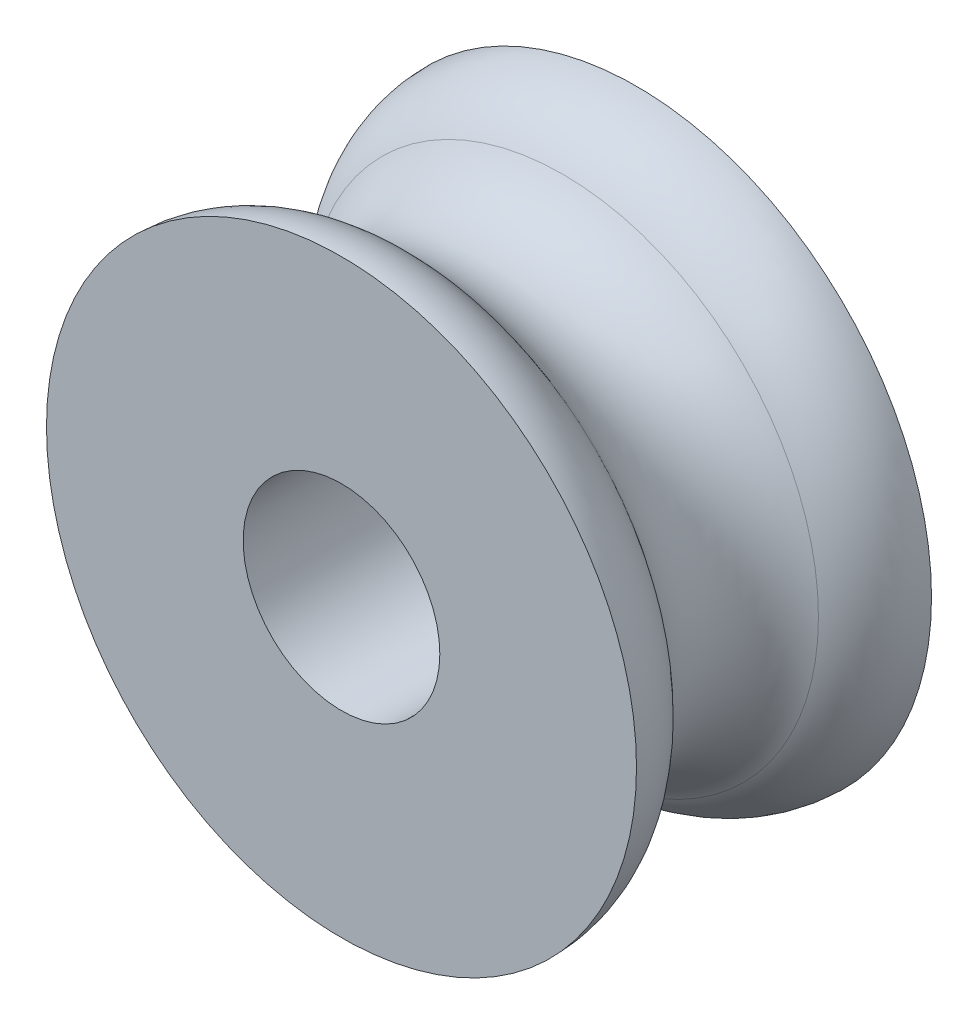
SolidWorks part; units mm, degrees
ref_plane "Front Plane" through (0, 0, 0) normal (0, 0, 1) x (1, 0, 0)
ref_plane "Top Plane" through (0, 0, 0) normal (0, 1, 0) x (1, 0, 0)
ref_plane "Right Plane" through (0, 0, 0) normal (1, 0, 0) x (0, 0, -1)
sketch "Sketch1" plane through (0, 0, 0) normal (1, 0, 0) x (0, 0, -1)
  line L0 (-3, 2) -> (3, 2)
  line L1 (3, 2) -> (3, 6)
  line L2 (-3, 6) -> (-3, 2)
  line L3 (0, 0) -> (5.2731, 0) construction
  arc A0 (3, 6) -> (1.5, 5.2) centre (3, 4.1937) ccw
  arc A1 (1.5, 5.2) -> (-1.5, 5.2) centre (0, 6.2062) cw
  arc A2 (-1.5, 5.2) -> (-3, 6) centre (-3, 4.1938) ccw
  point P9 (0, 2)
  dimension "D1" = 2
  dimension "D5" = 0.8
  dimension "D2" = 6
  dimension "D3" = 3
  dimension "D4" = 6
revolve "Revolve1" add sketch "Sketch1" angle 360 about L3
